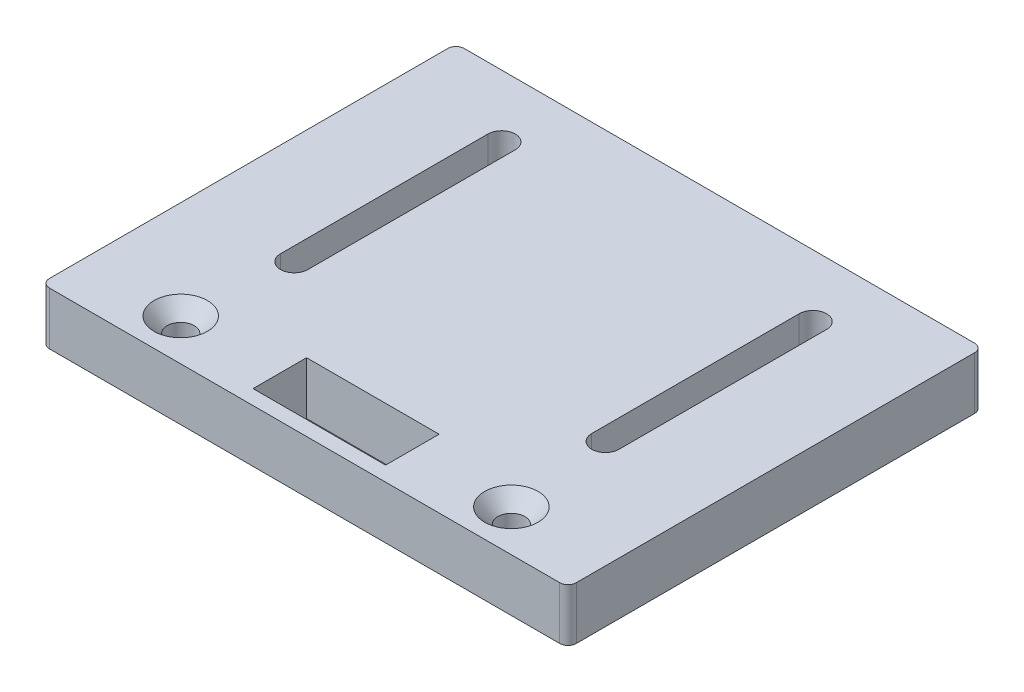
SolidWorks part; units mm, degrees
ref_plane "前基準面" through (0, 0, 0) normal (0, 0, 1) x (1, 0, 0)
ref_plane "上基準面" through (0, 0, 0) normal (0, 1, 0) x (1, 0, 0)
ref_plane "右基準面" through (0, 0, 0) normal (1, 0, 0) x (0, 0, -1)
sketch "Sketch1" plane through (0, 0, 0) normal (0, 1, 0) x (1, 0, 0)
  line L1 (0, 0) -> (127, 0)
  line L2 (0, 0) -> (0, 100)
  line L3 (0, 100) -> (127, 100)
  line L4 (127, 0) -> (127, 100)
extrude "Boss-Extrude1" add sketch "Sketch1" along normal blind 12.7
sketch "Sketch2" plane through (0, 12.7, 0) normal (0, 1, 0) x (1, 0, 0)
  line L6 (47.53, 10) -> (47.53, 16.45)
  line L7 (47.53, 16.45) -> (79.48, 16.45)
  line L8 (79.48, 10) -> (79.48, 16.45)
  line L9 (47.53, 10) -> (47.53, 3.55)
  line L10 (47.53, 3.55) -> (79.48, 3.55)
  line L11 (79.48, 3.55) -> (79.48, 10)
  dimension "D1" = 31.95
  dimension "D2" = 12.9
extrude "Cut-Extrude1" cut sketch "Sketch2" against normal blind 12.7
sketch "Sketch4" plane through (0, 12.7, 0) normal (0, 1, 0) x (1, 0, 0)
  point P7 (23.65, 9.9969)
  point P8 (103.35, 9.9969)
sketch "Sketch6" plane through (0, 12.7, 0) normal (0, 1, 0) x (1, 0, 0)
  line L1 (22.6908, 35) -> (22.6908, 85)
  line L2 (29.2908, 35) -> (29.2908, 85)
  line L10 (29.2908, 60) -> (97.7208, 60) construction
  line L13 (97.7208, 35) -> (97.7208, 85)
  line L14 (104.3091, 35.2777) -> (104.3091, 85.2777)
  line L15 (127, 100) -> (0, 100) construction
  line L16 (22.6908, 60) -> (0, 60.0215) construction
  line L17 (104.3091, 60.2777) -> (127, 60.2777) construction
  line L18 (127, 0) -> (127, 100) construction
  line L19 (0, 100) -> (0, 0) construction
  arc A6 (22.6908, 35) -> (29.2908, 35) centre (25.9908, 35) ccw
  arc A11 (29.2908, 85) -> (22.6908, 85) centre (25.9908, 85) ccw
  arc A12 (97.7208, 85) -> (104.3091, 85.2777) centre (101.0208, 85) cw
  arc A13 (104.3091, 35.2777) -> (97.7208, 35) centre (101.0208, 35) cw
  dimension "D1" = 50
  dimension "D2" = 3.3
  dimension "D4" = 3.3
  dimension "D6" = 15
  dimension "D7" = 22.6908
  dimension "D8" = 22.6909
  dimension "D9" = 15
  dimension "D3" = 68.43
  dimension "D5" = 50
extrude "Cut-Extrude2" cut sketch "Sketch6" against normal through all
fillet "Fillet1" radius 2 4 edges at (127, 6.35, -100) (127, 6.35, 0) (0, 6.35, 0) (0, 6.35, -100)
hole_wizard "CSK for 1/4 Flat Head Machine Screw1" positions "3DSketch1" profile "Sketch7" countersink size "1/4" standard "ANSI Inch" end condition through all
sketch3d "3DSketch1"
  point P0 (23.65, 12.7, -9.9969)
  point P3 (103.35, 12.7, -9.9969)
sketch "Sketch7" plane through (23.65, 12.7, -9.9969) normal (1, 0, 0) x (0, 0, 1)
  line L0 (0, 0) -> (0, 12.7)
  line L1 (0, 12.7) -> (3.2639, 12.7)
  line L2 (3.2639, 12.7) -> (3.2639, 3.6524)
  line L3 (3.2639, 3.6524) -> (6.4389, 0)
  line L5 (6.4389, 0) -> (0, 0)
  line L6 (-3.2639, 3.6524) -> (-6.4389, 0) construction
  line L11 (0, -6.35) -> (0, 107.95) construction
  dimension "Thru Hole Dia." = 6.5278
  dimension "Thru Hole Depth" = 12.7
  dimension "Near C'Sink Dia." = 12.8778
  dimension "Near C'Sink Angle" = 82
sketch "Sketch8" plane through (0, 12.7, 0) normal (0, 1, 0) x (1, 0, 0)
  point P0 (0, 0)
  point P4 (63.505, 10)
